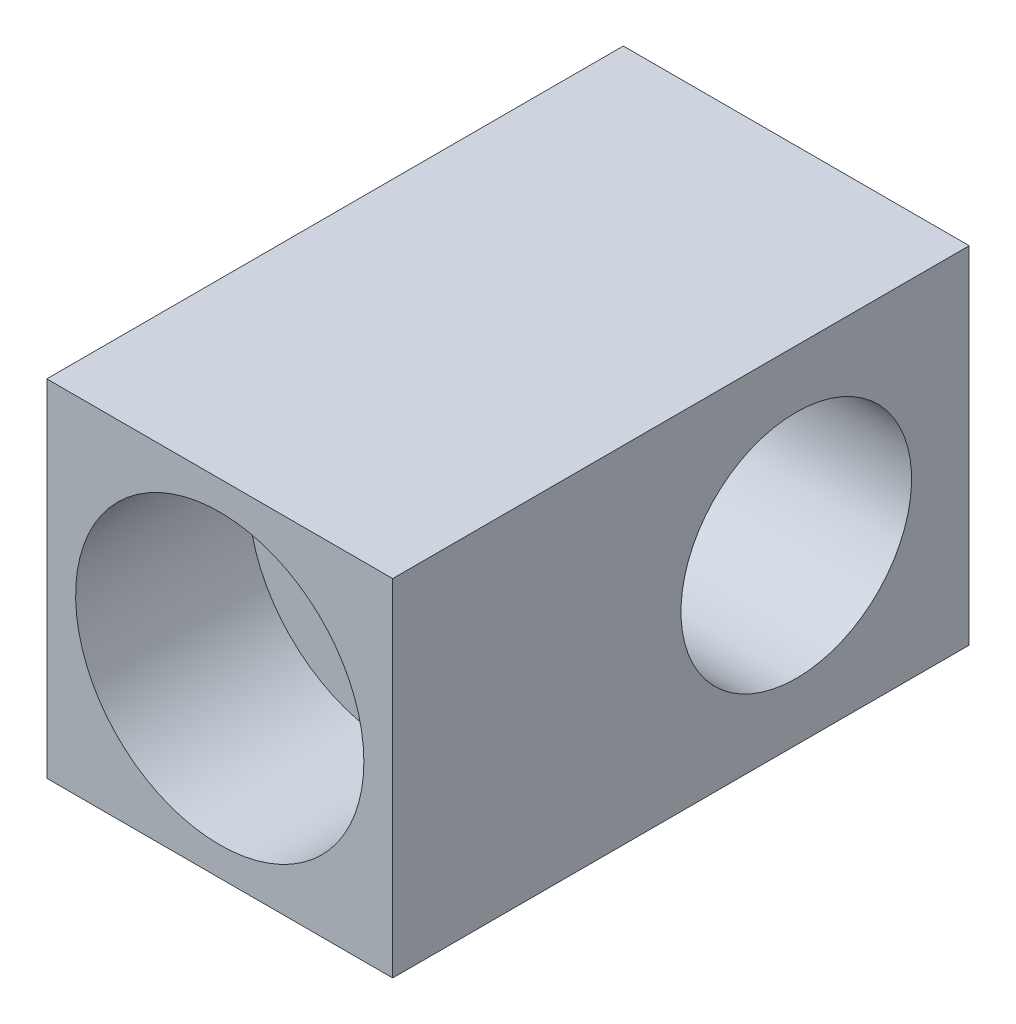
SolidWorks part; units mm, degrees
ref_plane "Front Plane" through (0, 0, 0) normal (0, 0, 1) x (1, 0, 0)
ref_plane "Top Plane" through (0, 0, 0) normal (0, 1, 0) x (1, 0, 0)
ref_plane "Right Plane" through (0, 0, 0) normal (1, 0, 0) x (0, 0, -1)
sketch "Sketch1" plane through (0, 0, 0) normal (0, 0, 1) x (1, 0, 0)
  line L1 (-1.5, 1.5) -> (1.5, 1.5)
  line L2 (-1.5, 1.5) -> (-1.5, -1.5)
  line L3 (-1.5, -1.5) -> (1.5, -1.5)
  line L4 (1.5, 1.5) -> (1.5, -1.5)
  line L5 (-1.5, 1.5) -> (1.5, -1.5) construction
  line L6 (-1.5, -1.5) -> (1.5, 1.5) construction
  point P0 (0, 0)
  dimension "D2" = 3
  dimension "D3" = 3
extrude "Boss-Extrude2" add sketch "Sketch1" along normal blind 6
sketch "Sketch2" plane through (1.5, 0, 0) normal (1, 0, 0) x (0, 0, -1)
  line L0 (-6, 0) -> (0, 0) construction
  line L1 (-6, -1.5) -> (-6, 1.5) construction
  line L2 (-3, 1.5) -> (-3, -1.5) construction
  line L3 (-6, 1.5) -> (0, 1.5) construction
  line L4 (-6, -1.5) -> (0, -1.5) construction
  line L5 (-3, 1.5) -> (0, 1.5) construction
  line L6 (-1.5, 1.5) -> (-1.5, -1.5) construction
  circle A0 centre (-1.5, 0) radius 1
  dimension "D1" = 2
extrude "Cut-Extrude1" cut sketch "Sketch2" against normal blind 6
sketch "Sketch3" plane through (0, 0, 6) normal (0, 0, 1) x (1, 0, 0)
  circle A0 centre (0, 0) radius 1.25
  dimension "D1" = 2.5
extrude "Cut-Extrude2" cut sketch "Sketch3" against normal blind 2.5
sketch "Sketch4" plane through (1.5, 0, 0) normal (1, 0, 0) x (0, 0, -1)
  line L0 (-6, 1.5) -> (-5, 1.5)
  line L1 (-6, 1.5) -> (0, 1.5) construction
  line L2 (-5, 1.5) -> (-5, -1.5)
  line L3 (-6, -1.5) -> (0, -1.5) construction
  line L4 (-5, -1.5) -> (-6, -1.5)
  line L5 (-6, -1.5) -> (-6, 1.5)
  circle A0 centre (-2.5, 0) radius 1
  circle A2 centre (-1.5, 0) radius 1
  line M3 (0, 1.5) -> (-6, 1.5)
  line M4 (-6, 1.5) -> (-6, -1.5)
  line M5 (-6, -1.5) -> (0, -1.5)
  dimension "D1" = 2
  dimension "D3" = 1
  dimension "D2" = 2.5
  dimension "D4" = 1
extrude "Cut-Extrude21" cut sketch "Sketch4" against normal blind 4 contours L2 M3 M4 M5
